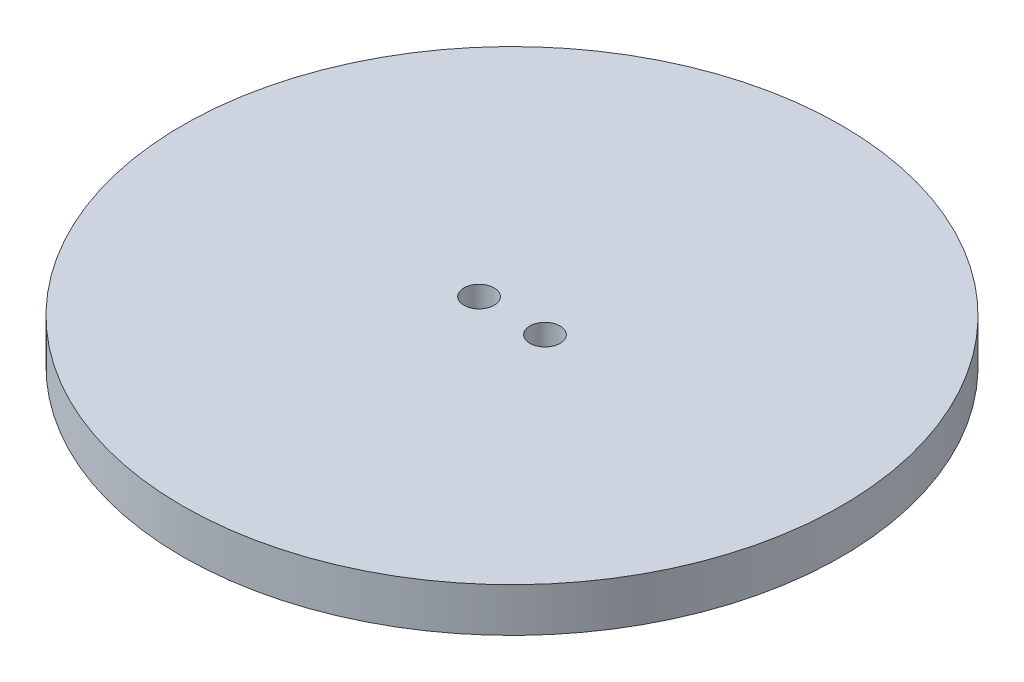
SolidWorks part; units mm, degrees
ref_plane "Front Plane" through (0, 0, 0) normal (0, 0, 1) x (1, 0, 0)
ref_plane "Top Plane" through (0, 0, 0) normal (0, 1, 0) x (1, 0, 0)
ref_plane "Right Plane" through (0, 0, 0) normal (1, 0, 0) x (0, 0, -1)
sketch "Sketch1" plane through (0, 0, 0) normal (0, 1, 0) x (1, 0, 0)
  circle A0 centre (0, 0) radius 60
  dimension "D1" = 120
extrude "Boss-Extrude1" add sketch "Sketch1" along normal blind 8
sketch "Sketch2" plane through (0, 8, 0) normal (0, 1, 0) x (1, 0, 0)
  circle A0 centre (6, 0) radius 2.75
  circle A1 centre (-6, 0) radius 2.75
  dimension "D1" = 6
  dimension "D2" = 6
  dimension "D3" = 5.5
  dimension "D4" = 5.5
extrude "Cut-Extrude1" cut sketch "Sketch2" against normal blind 8
